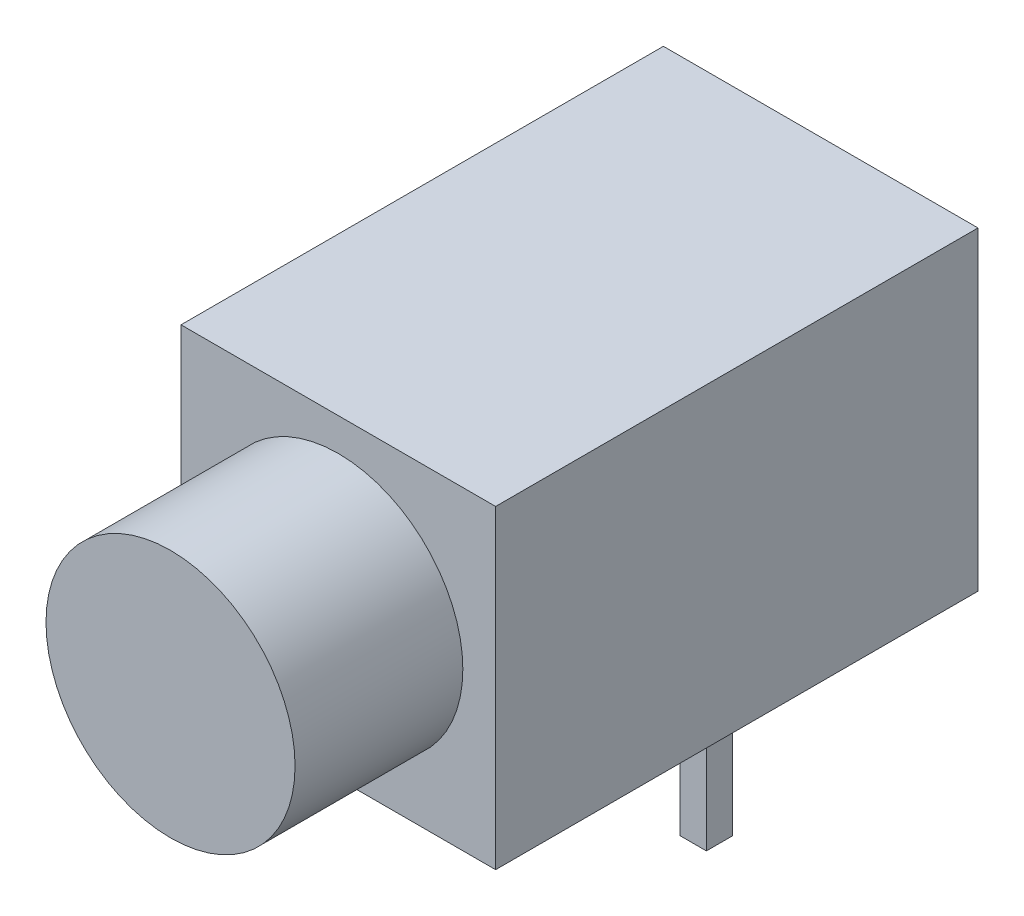
SolidWorks part; units mm, degrees
ref_plane "Front Plane" through (0, 0, 0) normal (0, 0, 1) x (1, 0, 0)
ref_plane "Top Plane" through (0, 0, 0) normal (0, 1, 0) x (1, 0, 0)
ref_plane "Right Plane" through (0, 0, 0) normal (1, 0, 0) x (0, 0, -1)
sketch "Sketch2" plane through (0, 0, 0) normal (0, 1, 0) x (1, 0, 0)
  line L1 (0, 0) -> (6, 0)
  line L2 (0, 0) -> (0, 9.2)
  line L3 (0, 9.2) -> (6, 9.2)
  line L4 (6, 0) -> (6, 9.2)
  dimension "D1" = 6
  dimension "D2" = 9.2
extrude "Boss-Extrude1" add sketch "Sketch2" along normal blind 6 contours L2 L1 L4 L3
sketch "Sketch3" plane through (0, 0, 0) normal (0, 0, 1) x (1, 0, 0)
  line L0 (0, 6) -> (6, 6) construction
  circle A0 centre (3, 3) radius 2.375
  point P5 (3, 6)
  dimension "D1" = 4.75
  dimension "D2" = 3
extrude "Boss-Extrude2" add sketch "Sketch3" along normal blind 3.2
sketch "Sketch4" plane through (0, 0, 0) normal (0, -1, 0) x (1, 0, 0)
  line L0 (0, 0) -> (6, 0) construction
  line L1 (1.48, -6) -> (1.98, -6)
  line L2 (1.48, -6) -> (1.48, -5.5)
  line L3 (1.48, -5.5) -> (1.98, -5.5)
  line L4 (1.98, -6) -> (1.98, -5.5)
  line L5 (4.02, -6) -> (4.52, -6)
  line L6 (4.02, -6) -> (4.02, -5.5)
  line L7 (4.02, -5.5) -> (4.52, -5.5)
  line L8 (4.52, -6) -> (4.52, -5.5)
  line L9 (0, 0) -> (0, -9.2) construction
  line L10 (6, 0) -> (6, -9.2) construction
  point P10 (1.73, -6)
  point P11 (4.27, -6)
  dimension "D1" = 5.5
  dimension "D2" = 5.5
  dimension "D3" = 0.5
  dimension "D4" = 0.5
  dimension "D5" = 0.5
  dimension "D6" = 0.5
  dimension "D7" = 2.54
  dimension "D8" = 1.48
  dimension "D9" = 1.48
extrude "Boss-Extrude3" add sketch "Sketch4" along normal blind 3.18
